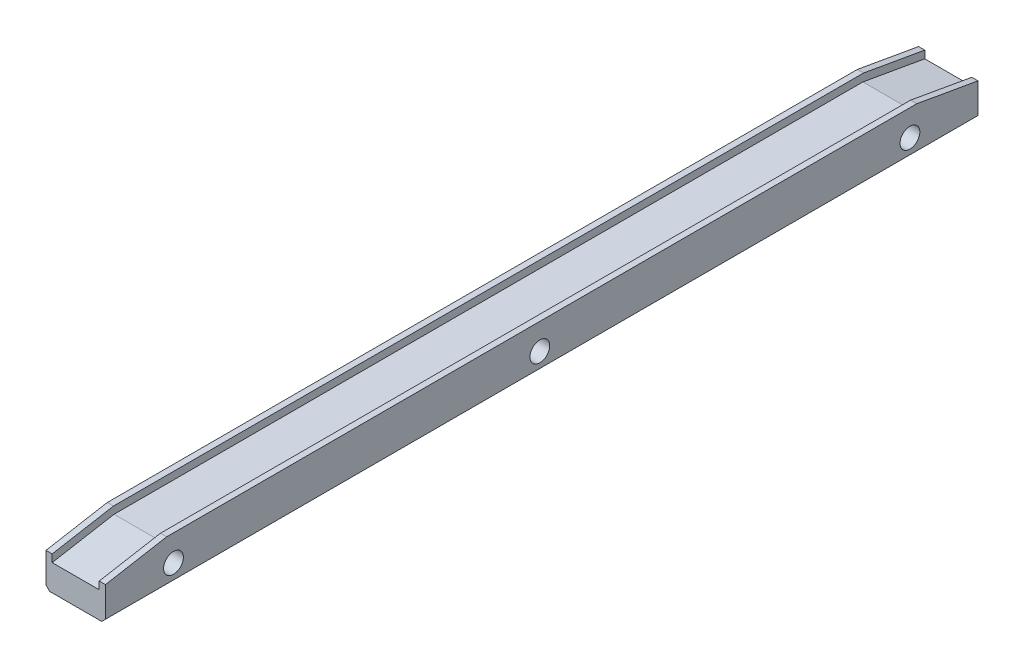
SolidWorks part; units mm, degrees
material "UHMW 15mm"
ref_plane "Plano frontal" through (0, 0, 0) normal (0, 0, 1) x (1, 0, 0)
ref_plane "Plano superior" through (0, 0, 0) normal (0, 1, 0) x (1, 0, 0)
ref_plane "Plano direito" through (0, 0, 0) normal (1, 0, 0) x (0, 0, -1)
sketch "Esboço1" plane through (0, 0, 0) normal (0, 0, 1) x (1, 0, 0)
  line L0 (-19, 0) -> (19, 0)
  line L1 (19, 0) -> (19, 6)
  line L2 (19, 6) -> (24, 6)
  line L3 (24, 6) -> (24, -30)
  line L4 (24, -30) -> (-24, -30)
  line L5 (0, -30) -> (0, 0) construction
  line L6 (-24, 6) -> (-24, -30)
  line L7 (-19, 6) -> (-24, 6)
  line L8 (-19, 0) -> (-19, 6)
  dimension "D1" = 38
  dimension "D2" = 48
  dimension "D3" = 6
  dimension "D4" = 30
extrude "Ressalto-extrusão1" add sketch "Esboço1" along normal mid plane 655
sketch "Esboço2" plane through (24, 0, 0) normal (1, 0, 0) x (0, 0, -1)
  line L0 (-327.5, -15) -> (327.5, -15) construction
  line L1 (-327.5, -30) -> (-327.5, 6) construction
  line L2 (327.5, -30) -> (327.5, 6) construction
  line L4 (-327.5, -36.6936) -> (-297.5, -36.6936) construction
  line L5 (-297.5, -36.6936) -> (-297.5, -15) construction
  line L6 (297.5, -15) -> (297.5, -36.6936) construction
  line L7 (297.5, -36.6936) -> (327.5, -36.6936) construction
  line L9 (-327.5, 0) -> (327.5, 0) construction
  circle A1 centre (-297.5, -15) radius 8
  circle A2 centre (297.5, -15) radius 8
  circle A3 centre (-1.5, -15) radius 8
  dimension "D1" = 15
  dimension "D2" = 16
  dimension "D3" = 296
  dimension "D4" = 299
  dimension "D5" = 30
extrude "Corte-extrusão1" cut sketch "Esboço2" against normal blind 655
sketch "Esboço3" plane through (0, 0, 327.5) normal (0, 0, 1) x (1, 0, 0)
  line L8 (-24, 6) -> (-24, -30)
  line L9 (-24, -30) -> (24, -30)
  line L10 (24, -30) -> (24, 6)
  line L11 (24, 6) -> (19, 6)
  line L12 (19, 6) -> (19, 0)
  line L13 (19, 0) -> (-19, 0)
  line L14 (-19, 0) -> (-19, 6)
  line L15 (-19, 6) -> (-24, 6)
  line L16 (-24, 6) -> (-24, -30)
  line L17 (-24, -30) -> (24, -30)
  line L18 (24, -30) -> (24, 6)
  line L19 (24, 6) -> (19, 6)
  line L20 (19, 6) -> (19, 0)
  line L21 (19, 0) -> (-19, 0)
  line L22 (-19, 0) -> (-19, 6)
  line L23 (-19, 6) -> (-24, 6)
  dimension "D1" = 0
extrude "Ressalto-extrusão2" add sketch "Esboço3" along normal blind 25
sketch "Esboço4" plane through (0, 0, -327.5) normal (0, 0, -1) x (-1, 0, 0)
  line L8 (24, -30) -> (24, 6)
  line L9 (24, 6) -> (19, 6)
  line L10 (19, 6) -> (19, 0)
  line L11 (19, 0) -> (-19, 0)
  line L12 (-19, 0) -> (-19, 6)
  line L13 (-19, 6) -> (-24, 6)
  line L14 (-24, 6) -> (-24, -30)
  line L15 (-24, -30) -> (24, -30)
  line L16 (24, -30) -> (24, 6)
  line L17 (24, 6) -> (19, 6)
  line L18 (19, 6) -> (19, 0)
  line L19 (19, 0) -> (-19, 0)
  line L20 (-19, 0) -> (-19, 6)
  line L21 (-19, 6) -> (-24, 6)
  line L22 (-24, 6) -> (-24, -30)
  line L23 (-24, -30) -> (24, -30)
  dimension "D1" = 0
extrude "Ressalto-extrusão3" add sketch "Esboço4" along normal blind 25
chamfer "Chanfro1" distance 50 angle 10 2 edges at (0, 0, -352.5) (0, 0, 352.5)
sketch "Esboço5" plane through (24, 0, 0) normal (1, 0, 0) x (0, 0, -1)
  line L0 (-352.5, -2.7238) -> (-303.0249, 6)
  line L1 (-352.5, -30) -> (-352.5, 6) construction
  line L2 (-352.5, 6) -> (352.5, 6) construction
  line L3 (-303.0249, 6) -> (-352.5, 6)
  line L4 (-352.5, 6) -> (-352.5, -2.7238)
  line L5 (-302.5, 0) -> (-352.5, -8.8163) construction
  line L7 (0, 0) -> (0, 180.3119) construction
  line L8 (352.5, 6) -> (352.5, -2.7238)
  line L9 (303.0249, 6) -> (352.5, 6)
  line L10 (352.5, -2.7238) -> (303.0249, 6)
  dimension "D1" = 6
extrude "Corte-extrusão2" cut sketch "Esboço5" against normal up to vertex
chamfer "Chanfro2" distance 3 angle 45 2 edges at (-24, -30, 0) (24, -30, 0)
